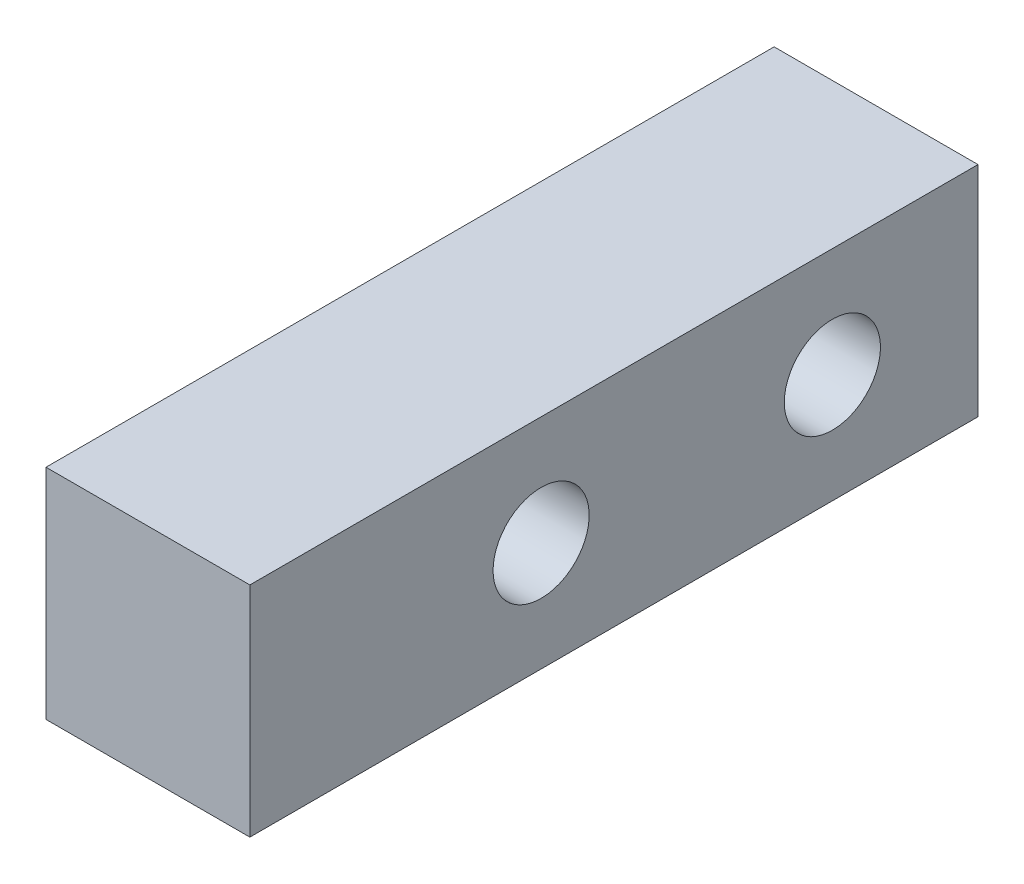
SolidWorks part; units mm, degrees
ref_plane "Front Plane" through (0, 0, 0) normal (0, 0, 1) x (1, 0, 0)
ref_plane "Top Plane" through (0, 0, 0) normal (0, 1, 0) x (1, 0, 0)
ref_plane "Right Plane" through (0, 0, 0) normal (1, 0, 0) x (0, 0, -1)
sketch "Sketch1" plane through (0, 0, 0) normal (0, 0, 1) x (1, 0, 0)
  line L5 (7, 7.5) -> (-7, 7.5)
  line L6 (7, 7.5) -> (7, -7.5)
  line L7 (7, -7.5) -> (-7, -7.5)
  line L8 (-7, 7.5) -> (-7, -7.5)
  line L9 (7, 7.5) -> (-7, -7.5) construction
  line L10 (7, -7.5) -> (-7, 7.5) construction
  point P0 (0, 0)
  dimension "D1" = 14
  dimension "15" = 15
extrude "Boss-Extrude1" add sketch "Sketch1" along normal blind 50
hole_wizard "CBORE for M6 Hex Head Bolt1" positions "Sketch2" profile "Sketch3" counterbore size "M6" standard "ISO" end condition through all
sketch "Sketch2" plane through (-7, 0, 0) normal (-1, 0, 0) x (0, 0, 1)
  point P0 (10, 0)
  point P2 (30, 0)
  dimension "D1" = 10
  dimension "D2" = 30
sketch "Sketch3" plane through (-7, 0, 10) normal (0, 1, 0) x (0, 0, 1)
  line L0 (0, 0) -> (0, 14)
  line L1 (0, 14) -> (3.3, 14)
  line L3 (3.3, 14) -> (3.3, 4)
  line L4 (7.2735, 4) -> (3.3, 4)
  line L5 (7.2735, 4) -> (7.2735, 0.025)
  line L6 (7.2735, 0.025) -> (7.2985, 0)
  line L7 (7.2985, 0) -> (0, 0)
  line L8 (-7.2735, 0.025) -> (-7.2985, 0) construction
  line L11 (0, -6.35) -> (0, 107.95) construction
  dimension "Thru Hole Dia." = 6.6
  dimension "Thru Hole Depth" = 14
  dimension "C'Bore Dia." = 14.547
  dimension "C'Bore Depth" = 4
  dimension "Near C'Sink Dia." = 14.597
  dimension "Near C'Sink Angle" = 90
